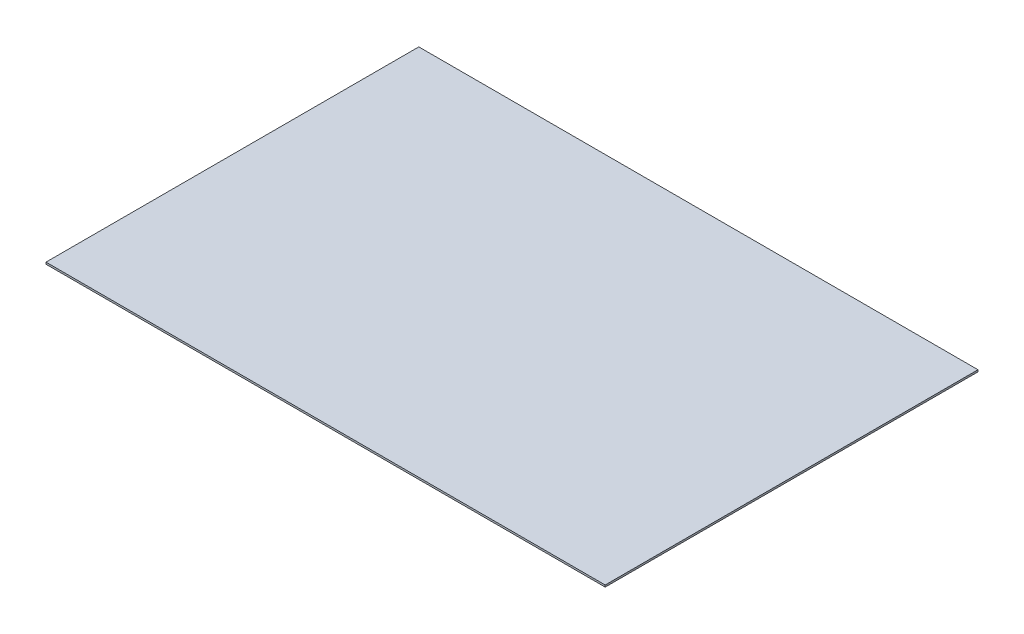
SolidWorks part; units mm, degrees
ref_plane "Спереди" through (0, 0, 0) normal (0, 0, 1) x (1, 0, 0)
ref_plane "Сверху" through (0, 0, 0) normal (0, 1, 0) x (1, 0, 0)
ref_plane "Справа" through (0, 0, 0) normal (1, 0, 0) x (0, 0, -1)
sketch "Эскиз1" plane through (0, 0, 0) normal (0, 1, 0) x (1, 0, 0)
  line L1 (-750, -500) -> (750, -500)
  line L2 (-750, -500) -> (-750, 500)
  line L3 (-750, 500) -> (750, 500)
  line L4 (750, -500) -> (750, 500)
  line L5 (-750, -500) -> (750, 500) construction
  line L6 (-750, 500) -> (750, -500) construction
  point P0 (0, 0)
  dimension "D1" = 1000
  dimension "D2" = 1500
extrude "Бобышка-Вытянуть1" add sketch "Эскиз1" along normal blind 5
